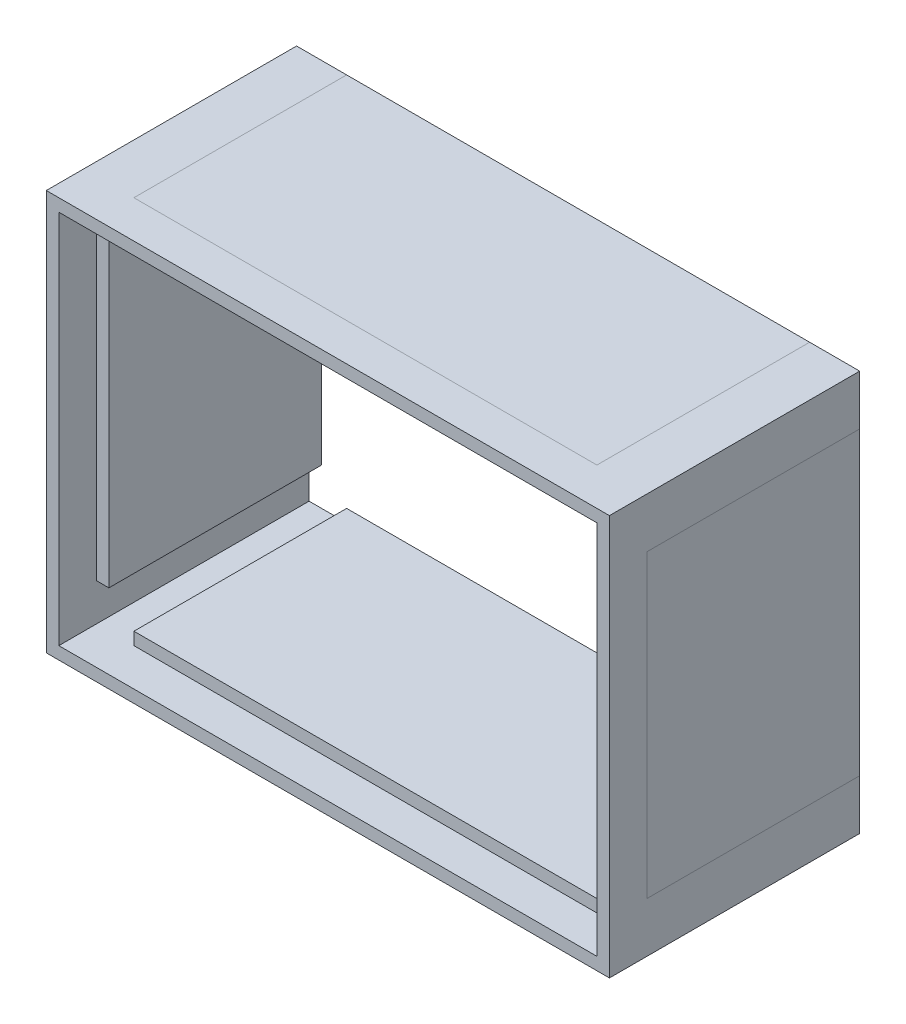
SolidWorks part; units mm, degrees
ref_plane "Front Plane" through (0, 0, 0) normal (0, 0, 1) x (1, 0, 0)
ref_plane "Top Plane" through (0, 0, 0) normal (0, 1, 0) x (1, 0, 0)
ref_plane "Right Plane" through (0, 0, 0) normal (1, 0, 0) x (0, 0, -1)
sketch "Sketch1" plane through (0, 0, 0) normal (0, 0, 1) x (1, 0, 0)
  line L1 (0, 0) -> (4500, 0)
  line L2 (0, 0) -> (0, 3200)
  line L3 (0, 3200) -> (4500, 3200)
  line L4 (4500, 0) -> (4500, 3200)
  line L5 (100, 100) -> (4400, 100)
  line L6 (100, 100) -> (100, 3100)
  line L7 (100, 3100) -> (4400, 3100)
  line L8 (4400, 100) -> (4400, 3100)
  dimension "D1" = 100
  dimension "D2" = 100
  dimension "D3" = 100
  dimension "D4" = 100
  dimension "D5" = 3000
  dimension "D6" = 4300
extrude "Boss-Extrude1" add sketch "Sketch1" along normal blind 2000
sketch "Sketch2" plane through (0, 3100, 0) normal (0, -1, 0) x (1, 0, 0)
  line L0 (4400, 0) -> (100, 0) construction
  line L1 (400, 0) -> (4100, 0)
  line L2 (400, 0) -> (400, 1700)
  line L3 (400, 1700) -> (4100, 1700)
  line L4 (4100, 0) -> (4100, 1700)
  line L5 (100, 2000) -> (100, 0) construction
  line L6 (4400, 2000) -> (4400, 0) construction
  line L7 (4400, 2000) -> (100, 2000) construction
  dimension "D1" = 300
  dimension "D2" = 300
  dimension "D3" = 300
extrude "Cut-Extrude1" cut sketch "Sketch2" against normal through all both and the other way through all
sketch "Sketch3" plane through (0, 0, 0) normal (-1, 0, 0) x (0, 0, 1)
  line L0 (2000, 100) -> (0, 100) construction
  line L1 (0, 400) -> (1700, 400)
  line L2 (0, 400) -> (0, 2800)
  line L3 (0, 2800) -> (1700, 2800)
  line L4 (1700, 400) -> (1700, 2800)
  line L5 (2000, 3100) -> (0, 3100) construction
  line L6 (2000, 3100) -> (2000, 100) construction
  line L7 (0, 3200) -> (0, 0) construction
  dimension "D1" = 300
  dimension "D2" = 300
  dimension "D3" = 300
extrude "Cut-Extrude2" cut sketch "Sketch3" against normal through all both and the other way through all
sketch "Sketch4" plane through (0, 0, 1700) normal (0, 0, -1) x (-1, 0, 0)
  line L0 (-400, 100) -> (-400, 0) construction
  line L1 (-4100, 0) -> (-400, 0)
  line L2 (-4100, 0) -> (-4100, 200)
  line L3 (-4100, 200) -> (-400, 200)
  line L4 (-400, 0) -> (-400, 200)
  line L5 (0, 400) -> (-200, 400)
  line L6 (0, 400) -> (0, 2800)
  line L7 (0, 2800) -> (-200, 2800)
  line L8 (-200, 400) -> (-200, 2800)
  line L9 (-400, 3200) -> (-4100, 3200)
  line L10 (-400, 3200) -> (-400, 3000)
  line L11 (-400, 3000) -> (-4100, 3000)
  line L12 (-4100, 3200) -> (-4100, 3000)
  line L13 (-4500, 400) -> (-4300, 400)
  line L14 (-4500, 400) -> (-4500, 2800)
  line L15 (-4500, 2800) -> (-4300, 2800)
  line L16 (-4300, 400) -> (-4300, 2800)
  line L17 (-100, 2800) -> (0, 2800) construction
  line L18 (-4100, 3200) -> (-4100, 3100) construction
  line L19 (-4500, 2800) -> (-4400, 2800) construction
  dimension "D1" = 200
  dimension "D2" = 200
  dimension "D3" = 200
  dimension "D4" = 200
extrude "Boss-Extrude2" add sketch "Sketch4" along normal up to surface (1700 mm away) separate body up to face at (4333.3333, 166.6667, 0)
